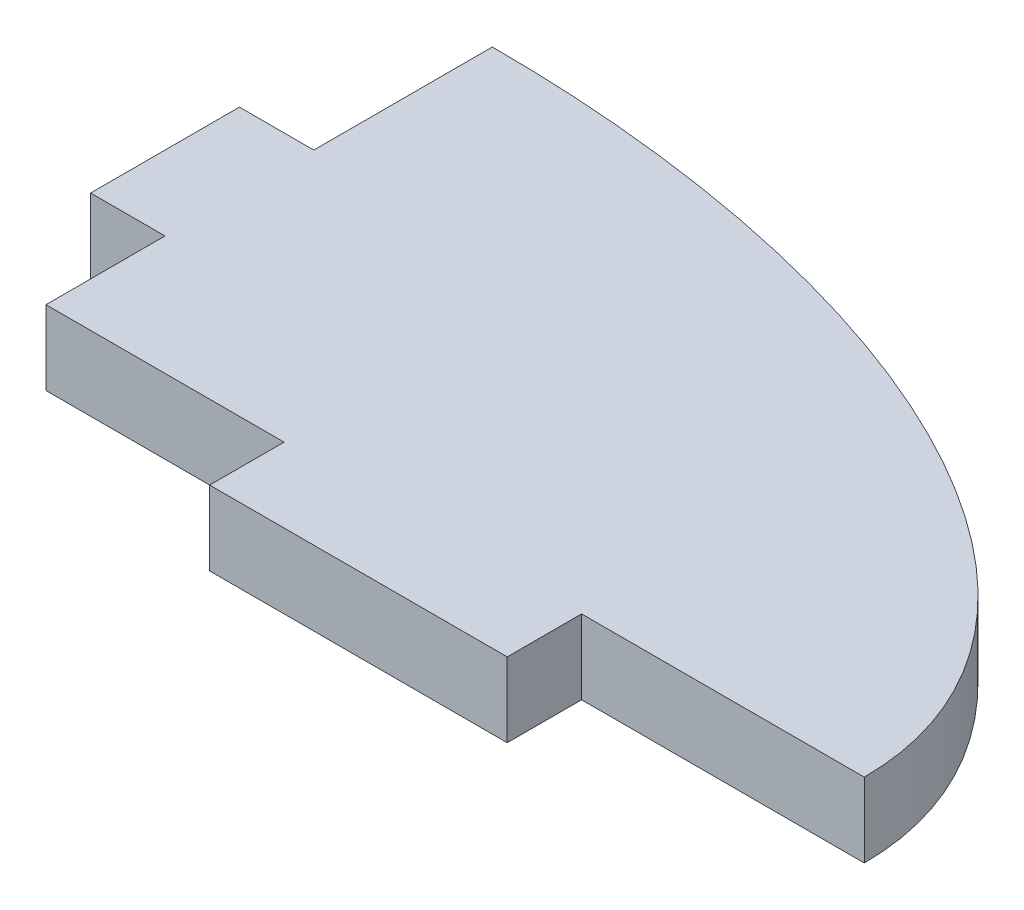
SolidWorks part; units mm, degrees
ref_plane "前视基准面" through (0, 0, 0) normal (0, 0, 1) x (1, 0, 0)
ref_plane "上视基准面" through (0, 0, 0) normal (0, 1, 0) x (1, 0, 0)
ref_plane "右视基准面" through (0, 0, 0) normal (1, 0, 0) x (0, 0, -1)
sketch "Sketch5" plane through (0, 0, 0) normal (0, 1, 0) x (1, 0, 0)
  line L0 (0, 0) -> (0, 19.05)
  line L1 (0, 0) -> (34.925, 0)
  ellipse E0 centre (0, 0) end of major axis (-34.925, 0) minor radius 19.05 (34.925, 0) -> (0, 19.05) ccw
  dimension "D1" = 19.05
  dimension "D2" = 34.925
extrude "Boss-Extrude2" add sketch "Sketch5" along normal blind 3.175
sketch "Sketch6" plane through (0, 3.175, 0) normal (0, 1, 0) x (1, 0, 0)
  line L0 (0, 19.05) -> (0, 0) construction
  line L1 (0, 5.08) -> (-3.175, 5.08)
  line L2 (0, 5.08) -> (0, 11.43)
  line L3 (0, 11.43) -> (-3.175, 11.43)
  line L4 (-3.175, 5.08) -> (-3.175, 11.43)
  line L5 (0, 0) -> (34.925, 0) construction
  line L7 (10.16, 0) -> (22.86, 0)
  line L8 (10.16, 0) -> (10.16, -3.175)
  line L9 (10.16, -3.175) -> (22.86, -3.175)
  line L10 (22.86, 0) -> (22.86, -3.175)
  dimension "D1" = 6.35
  dimension "D2" = 3.175
  dimension "D3" = 5.08
  dimension "D4" = 12.7
  dimension "D5" = 3.175
  dimension "D6" = 10.16
extrude "Boss-Extrude4" add sketch "Sketch6" against normal blind 3.175
